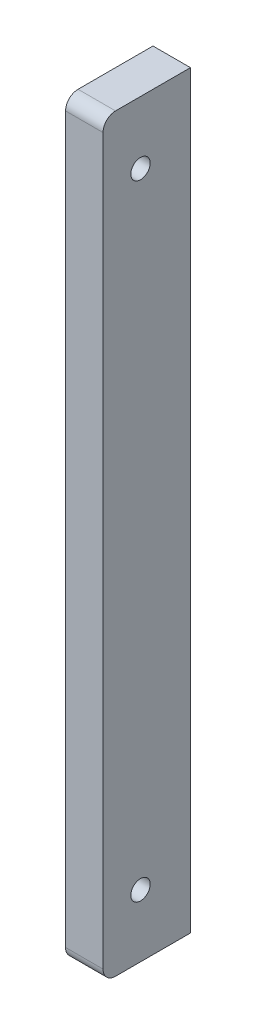
SolidWorks part; units mm, degrees
ref_plane "Front Plane" through (0, 0, 0) normal (0, 0, 1) x (1, 0, 0)
ref_plane "Top Plane" through (0, 0, 0) normal (0, 1, 0) x (1, 0, 0)
ref_plane "Right Plane" through (0, 0, 0) normal (1, 0, 0) x (0, 0, -1)
sketch "Sketch1" plane through (0, 0, 0) normal (1, 0, 0) x (0, 0, -1)
  line L0 (-14, -60) -> (-14, 60)
  line L1 (55, 0) -> (-55, 0) construction
  line L4 (-14, 60) -> (0, 60)
  line L5 (0, 55) -> (0, -55) construction
  line L6 (0, 60) -> (0, -60)
  line L7 (-14, -60) -> (0, -60)
  circle A0 centre (-8, 50) radius 1.55
  circle A1 centre (-8, -50) radius 1.55
  point P16 (0, 0)
  point P19 (-14, 0)
  dimension "D5" = 50
  dimension "D7" = 3.1
  dimension "D2" = 60
  dimension "D4" = 14
  dimension "D6" = 8
extrude "Boss-Extrude1" add sketch "Sketch1" along normal blind 6
fillet "Fillet1" radius 2 2 edges at (3, -60, 14) (3, 60, 14)
